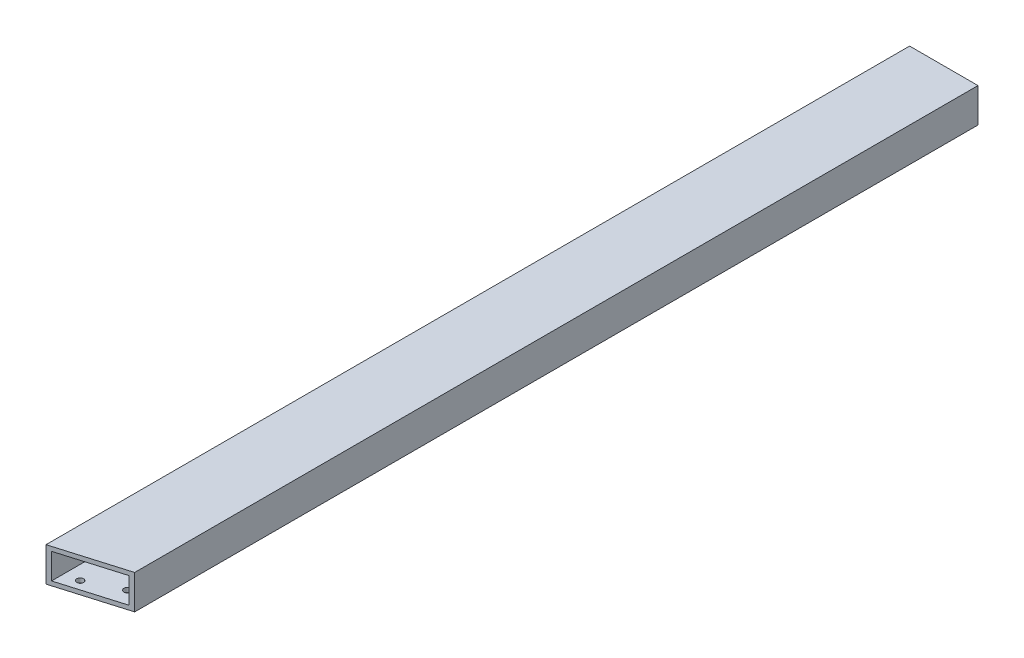
SolidWorks part; units mm, degrees
material "1060 Alloy"
ref_plane "Front Plane" through (0, 0, 0) normal (0, 0, 1) x (1, 0, 0)
ref_plane "Top Plane" through (0, 0, 0) normal (0, 1, 0) x (1, 0, 0)
ref_plane "Right Plane" through (0, 0, 0) normal (1, 0, 0) x (0, 0, -1)
sketch "Sketch1" plane through (0, 0, 0) normal (0, 0, 1) x (1, 0, 0)
  line L0 (-22.225, 9.525) -> (22.225, 9.525)
  line L2 (-25.4, 12.7) -> (25.4, 12.7)
  line L3 (-25.4, 12.7) -> (-25.4, -12.7)
  line L4 (-25.4, -12.7) -> (25.4, -12.7)
  line L5 (25.4, 12.7) -> (25.4, -12.7)
  line L10 (22.225, 9.525) -> (22.225, -9.525)
  line L11 (-22.225, -9.525) -> (22.225, -9.525)
  line L12 (-22.225, 9.525) -> (-22.225, -9.525)
  point P12 (0, 12.7)
  point P14 (25.4, 0)
  dimension "Wall Thickness" = 3.175
  dimension "Outside Width" = 50.8
  dimension "Outside Height" = 25.4
  dimension "Inside Height" = 19.05
  dimension "Inside Width" = 44.45
sketch "Sketch2" plane through (0, 0, 0) normal (1, 0, 0) x (0, 0, -1)
  line L0 (320.675, 0) -> (-320.675, 0)
  point P4 (0, 0)
  point P7 (-320.675, 0)
  point P10 (320.675, 0)
  dimension "Length" = 641.35
sketch "Sketch3" plane through (0, 0, 0) normal (0, 0, 1) x (1, 0, 0)
  line L21 (25.4, 12.7) -> (-25.4, 12.7)
  line L22 (25.4, -12.7) -> (25.4, 12.7)
  line L23 (-25.4, -12.7) -> (25.4, -12.7)
  line L24 (-25.4, 12.7) -> (-25.4, -12.7)
  line L25 (25.4, 12.7) -> (-25.4, 12.7)
  line L26 (25.4, -12.7) -> (25.4, 12.7)
  line L27 (-25.4, -12.7) -> (25.4, -12.7)
  line L28 (-25.4, 12.7) -> (-25.4, -12.7)
  line L29 (22.225, 9.525) -> (-22.225, 9.525)
  line L30 (22.225, -9.525) -> (22.225, 9.525)
  line L31 (-22.225, -9.525) -> (22.225, -9.525)
  line L32 (-22.225, 9.525) -> (-22.225, -9.525)
  line L33 (22.225, 9.525) -> (-22.225, 9.525)
  line L34 (22.225, -9.525) -> (22.225, 9.525)
  line L35 (-22.225, -9.525) -> (22.225, -9.525)
  line L36 (-22.225, 9.525) -> (-22.225, -9.525)
  dimension "D1" = 0
  dimension "D2" = 0
extrude "Boss-Extrude1" add sketch "Sketch3" along normal up to vertex (320.675 mm away) and the other way up to vertex (320.675 mm away) up to point (0, 0, 320.675) other way up to point (0, 0, -320.675)
sketch "Drawing Reference" plane through (0, 0, 0) normal (1, 0, 0) x (0, 0, -1)
  line L0 (-320.675, 0) -> (320.675, 0) construction
  line L1 (0, -12.7) -> (0, 12.7) construction
  line L2 (-320.675, -12.7) -> (320.675, -12.7) construction
  line L5 (-320.675, 12.7) -> (320.675, 12.7) construction
  point P7 (-284.099, 0)
  point P8 (284.099, 0)
  dimension "D1" = 36.576
sketch "Sketch4" plane through (0, 12.7, 0) normal (0, 1, 0) x (1, 0, 0)
  line L0 (-25.4, -320.675) -> (25.4, -305.6274)
  line L1 (25.4, -320.675) -> (25.4, 320.675) construction
  line L2 (25.4, -320.675) -> (-25.4, -320.675)
  dimension "D1" = 16.5
extrude "Cut-Extrude1" cut sketch "Sketch4" against normal through all and the other way through all flip side to cut
sketch "Sketch6" plane through (0, -12.7, 0) normal (0, -1, 0) x (1, 0, 0)
  line L0 (25.4, 305.6274) -> (22.1108, 294.5233) construction
  line L1 (25.4, 279.2824) -> (22.225, 279.2824) construction
  line L2 (25.4, 305.6274) -> (25.4, -320.675) construction
  line L3 (22.225, 279.2824) -> (22.225, 313.1512) construction
  line L4 (22.1108, 294.5233) -> (11.811, 297.5742) construction
  line L5 (-11.811, 250.3501) -> (-11.811, 328.3651) construction
  line L6 (-25.4, 320.675) -> (-27.5213, 313.5136) construction
  line L7 (-25.4, 287.6223) -> (-22.225, 287.6223) construction
  line L8 (-25.4, 320.675) -> (-25.4, -320.675) construction
  line L9 (-22.225, 287.6223) -> (-22.225, 328.3651) construction
  line L10 (-27.5213, 313.5136) -> (-11.811, 308.86) construction
  line L11 (11.811, 250.3501) -> (11.811, 313.1512) construction
  line L12 (-27.5213, 313.5136) -> (-36.5388, 283.071) construction
  line L13 (22.1108, 294.5233) -> (13.0933, 264.0807) construction
  line L14 (-37.6746, 250.3501) -> (48.6057, 250.3501) construction
  line L15 (-11.811, 287.6223) -> (-11.811, 328.3651) construction
  line L16 (11.811, 279.2824) -> (11.811, 313.1512) construction
  line L17 (-36.5388, 283.071) -> (-11.811, 275.7463) construction
  line L18 (13.0933, 264.0807) -> (11.811, 264.4606) construction
  point P10 (0, 0)
  point P31 (0, 0)
  dimension "D1" = 10.414
  dimension "D2" = 10.414
hole_wizard "#10 Clearance Hole1" positions "Sketch7" profile "Sketch8" hole size "#10" standard "ANSI Inch"
sketch "Sketch7" plane through (0, -12.7, 0) normal (0, -1, 0) x (-1, 0, 0)
  point P0 (-11.811, -264.4606)
  point P3 (11.811, -275.7463)
  point P7 (-11.811, -297.5742)
  point P10 (11.811, -308.86)
sketch "Sketch8" plane through (11.811, -12.7, 264.4606) normal (1, 0, 0) x (0, 0, -1)
  line L0 (0, 0) -> (0, 6.5757)
  line L1 (0, 6.5757) -> (2.4892, 5.08)
  line L2 (2.4892, 5.08) -> (2.4892, 0)
  line L5 (2.4892, 0) -> (0, 0)
  line L10 (0, 6.5757) -> (-2.4892, 5.08) construction
  line L11 (0, -6.35) -> (0, 107.95) construction
  dimension "Hole Dia." = 4.9784
  dimension "Hole Depth" = 5.08
  dimension "Drill Angle" = 118
equation "\"D1@Drawing Reference\"=\"Outside Width@Sketch1\" * 0.72"
